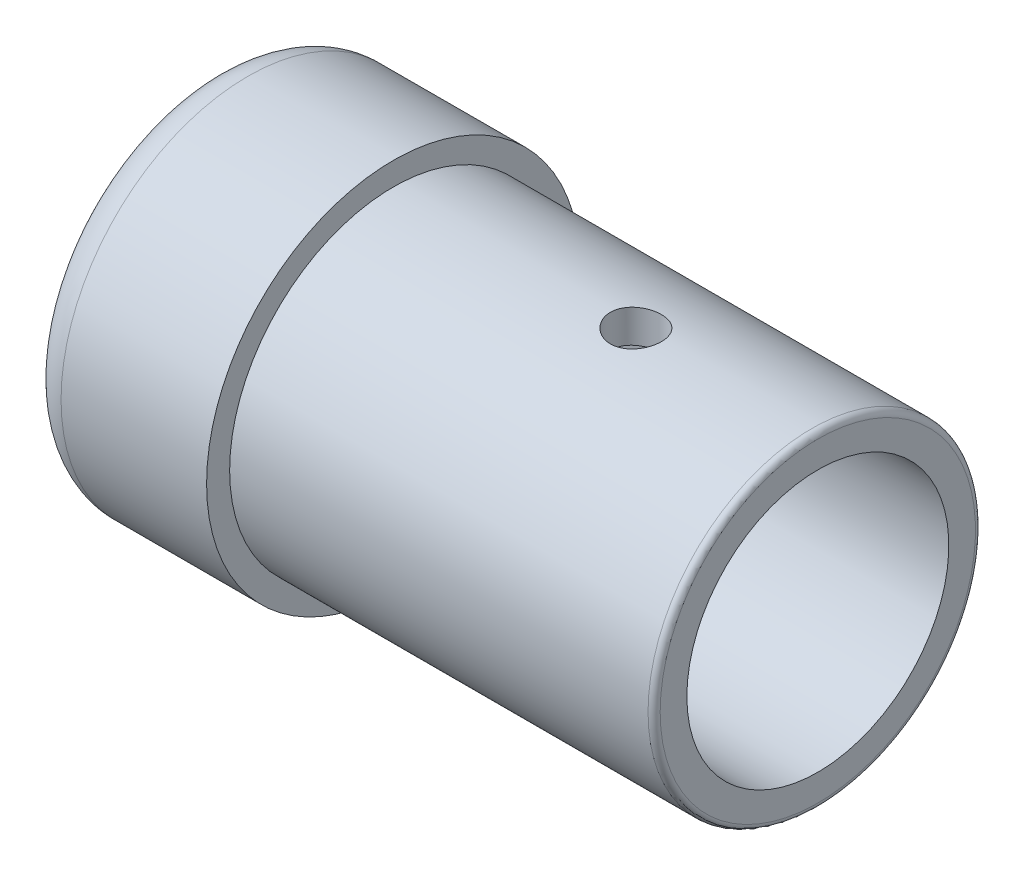
SolidWorks part; units mm, degrees
material "Alumina"
ref_plane "Plano frontal" through (0, 0, 0) normal (0, 0, 1) x (1, 0, 0)
ref_plane "Plano superior" through (0, 0, 0) normal (0, 1, 0) x (1, 0, 0)
ref_plane "Plano direito" through (0, 0, 0) normal (1, 0, 0) x (0, 0, -1)
sketch "Esboço1" plane through (0, 0, 0) normal (0, 0, 1) x (1, 0, 0)
  line L0 (0, 10.8) -> (0, 15.4)
  line L1 (0, 15.4) -> (15, 15.4)
  line L2 (15, 15.4) -> (15, 13.5)
  line L3 (15, 13.5) -> (50, 13.5)
  line L4 (50, 13.5) -> (50, 10.8)
  line L5 (50, 10.8) -> (0, 10.8)
  line L6 (0, 0) -> (33.9415, 0) construction
  dimension "D1" = 15.4
  dimension "D2" = 13.5
  dimension "D3" = 2.7
  dimension "D4" = 15
  dimension "D5" = 50
revolve "Revolução1" add sketch "Esboço1" angle 360 about L6
hole_wizard "Furo roscado de M51" positions "Esboço2" profile "Esboço3" tap size "M5" standard "DIN"
sketch "Esboço2" plane through (0, 0, 0) normal (0, 1, 0) x (1, 0, 0)
  line L0 (50, -13.5) -> (50, 13.5) construction
  point P0 (35, 0)
  dimension "D1" = 15
sketch "Esboço3" plane through (35, 0, 0) normal (1, 0, 0) x (0, 0, -1)
  line L0 (0, 0) -> (0, 15.4)
  line L1 (0, 15.4) -> (2.1, 15.4)
  line L2 (2.1, 15.4) -> (2.1, 0)
  line L5 (2.1, 0) -> (0, 0)
  line L11 (0, -6.35) -> (0, 107.95) construction
  dimension "Thru Tap Drill Dia." = 4.2
  dimension "Thru Tap Drill Depth" = 15.4
cosmetic thread "Rosca de furo1" parameters "D2"=5
fillet "Filete1" radius 3 1 edges at (0, 0, 15.4)
fillet "Filete2" radius 0.5 1 edges at (50, 0, 13.5)
